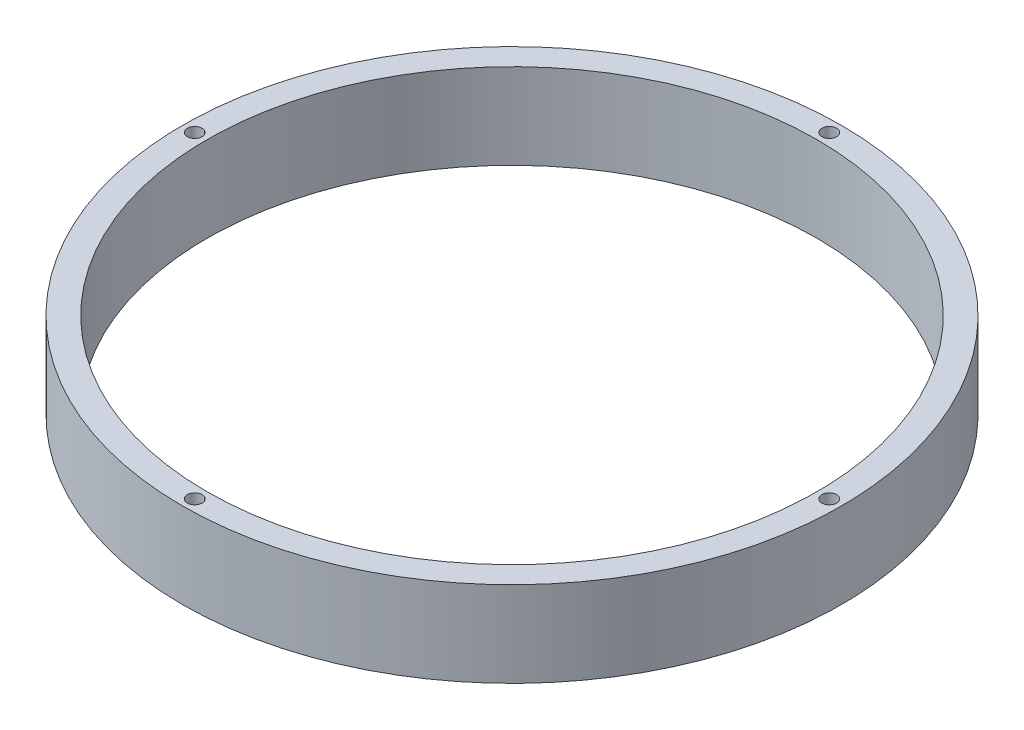
SolidWorks part; units mm, degrees
ref_plane "Front Plane" through (0, 0, 0) normal (0, 0, 1) x (1, 0, 0)
ref_plane "Top Plane" through (0, 0, 0) normal (0, 1, 0) x (1, 0, 0)
ref_plane "Right Plane" through (0, 0, 0) normal (1, 0, 0) x (0, 0, -1)
sketch "Sketch1" plane through (0, 0, 0) normal (0, 1, 0) x (1, 0, 0)
  circle A0 centre (0, 0) radius 67
  circle A1 centre (0, 0) radius 62
  circle A6 centre (0, 0) radius 62 construction
  circle A7 centre (0, 0) radius 62 construction
  dimension "D1" = 134
extrude "Boss-Extrude1" add sketch "Sketch1" along normal up to surface (13.5 mm away)
sketch "Sketch2" plane through (0, 13.5, 0) normal (0, 1, 0) x (1, 0, 0)
  circle A0 centre (0, 0) radius 62
  circle A1 centre (0, 0) radius 62 construction
  circle A2 centre (0, 0) radius 67
  circle A5 centre (0, 0) radius 67 construction
  circle A6 centre (0, 0) radius 23.5 construction
  circle A7 centre (0, 0) radius 23.5 construction
extrude "Boss-Extrude2" add sketch "Sketch2" along normal up to surface (3.875 mm away)
sketch "Sketch3" plane through (0, 0, 0) normal (0, -1, 0) x (1, 0, 0)
  line L0 (0, 0) -> (0, 62) construction
  line L1 (0, 62) -> (0, 67) construction
  circle A0 centre (0, 64.5) radius 1.5
  circle A3 centre (0, 0) radius 67 construction
  circle A4 centre (0, 0) radius 67 construction
  circle A5 centre (64.5, 0) radius 1.5
  circle A6 centre (0, -64.5) radius 1.5
  circle A7 centre (-64.5, 0) radius 1.5
  circle A8 centre (0, 0) radius 62 construction
  circle A9 centre (0, 0) radius 62 construction
  point P10 (0, 64.5)
  dimension "D1" = 3
  dimension "D2" = 4
extrude "Cut-Extrude1" cut sketch "Sketch3" against normal through all
sketch "Sketch4" [suppressed] plane through (0, 13.5, 0) normal (0, -1, 0) x (1, 0, 0)
  circle A0 centre (0, 0) radius 36.75 construction
  circle A1 centre (0, 0) radius 41.25
  circle A2 centre (0, 0) radius 32.25
  dimension "D1" = 73.5
  dimension "D2" = 4.5
  dimension "D3" = 4.5
extrude "Cut-Extrude2" [suppressed] cut sketch "Sketch4" against normal blind 3
